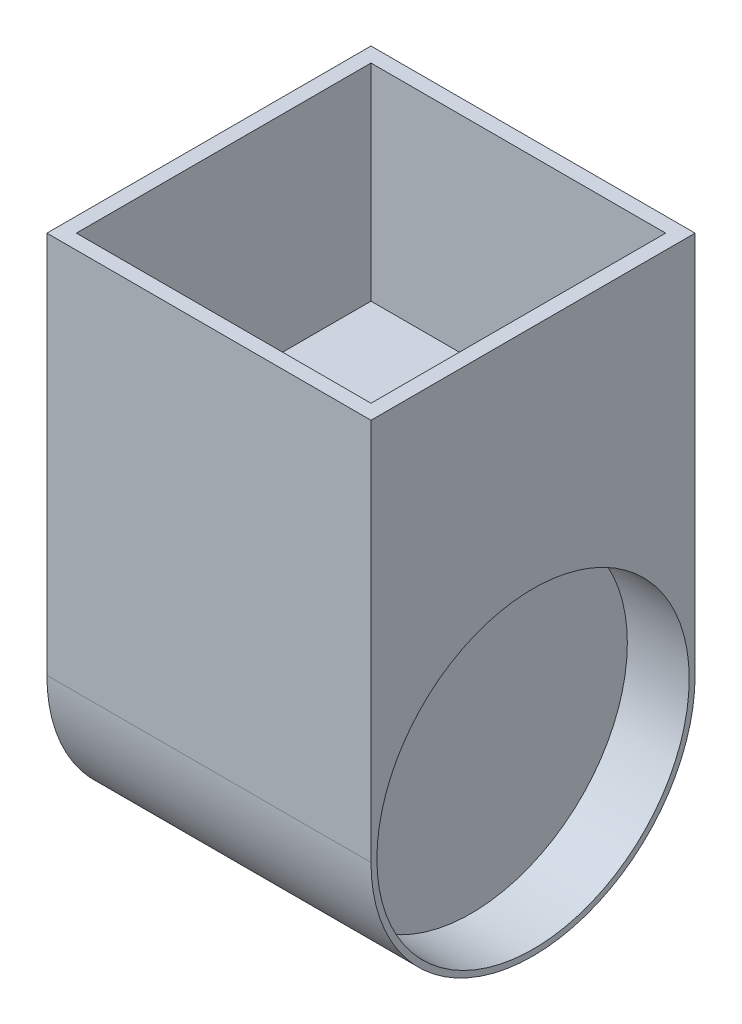
SolidWorks part; units mm, degrees
ref_plane "Front Plane" through (0, 0, 0) normal (0, 0, 1) x (1, 0, 0)
ref_plane "Top Plane" through (0, 0, 0) normal (0, 1, 0) x (1, 0, 0)
ref_plane "Right Plane" through (0, 0, 0) normal (1, 0, 0) x (0, 0, -1)
sketch "Sketch1" plane through (0, 0, 0) normal (1, 0, 0) x (0, 0, -1)
  line L3 (55, 129.9777) -> (55, 0)
  line L4 (-55, 0) -> (-55, 129.9777)
  line L5 (-55, 129.9777) -> (55, 129.9777)
  arc A1 (55, 0) -> (-55, 0) centre (0, 0) cw
extrude "Boss-Extrude1" add sketch "Sketch1" along normal blind 110 contours L3 A1 L4 L5
sketch "Sketch2" plane through (0, 129.9777, 0) normal (0, 1, 0) x (1, 0, 0)
  line L0 (5, 50) -> (105, 50)
  line L1 (105, 50) -> (105, -50)
  line L2 (105, -50) -> (5, -50)
  line L3 (5, -50) -> (5, 50)
  line L4 (110, -55) -> (110, 55) construction
  line L5 (110, 55) -> (0, 55) construction
  dimension "D1" = 100
  dimension "D2" = 100
  dimension "D3" = 5
  dimension "D4" = 5
extrude "Cut-Extrude1" cut sketch "Sketch2" against normal blind 70
sketch "Sketch3" plane through (110, 0, 0) normal (1, 0, 0) x (0, 0, -1)
  circle A0 centre (0, 0) radius 53
  arc A1 (-55, 0) -> (55, 0) centre (0, 0) ccw construction
  point P6 (0, -55)
  dimension "D1" = 55
extrude "Cut-Extrude2" cut sketch "Sketch3" against normal blind 21
